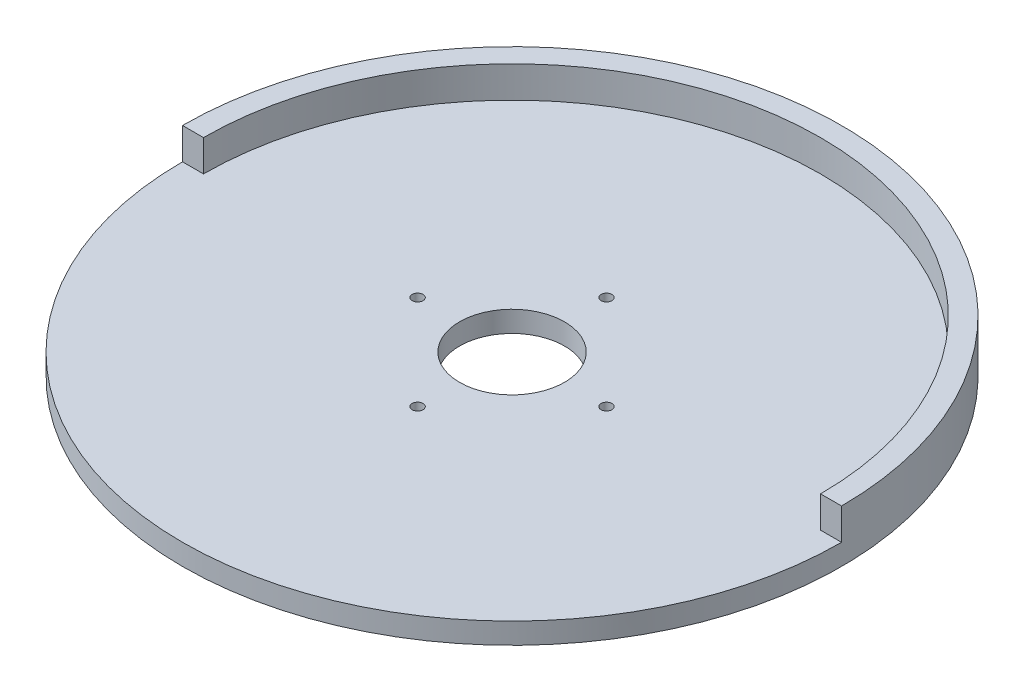
SolidWorks part; units mm, degrees
ref_plane "Front Plane" through (0, 0, 0) normal (0, 0, 1) x (1, 0, 0)
ref_plane "Top Plane" through (0, 0, 0) normal (0, 1, 0) x (1, 0, 0)
ref_plane "Right Plane" through (0, 0, 0) normal (1, 0, 0) x (0, 0, -1)
sketch "Sketch2" plane through (0, 0, 0) normal (0, 1, 0) x (1, 0, 0)
  circle A0 centre (0, 0) radius 65
  circle A1 centre (0, 0) radius 147
  circle A2 centre (0, 0) radius 157
  dimension "D1" = 82
  dimension "D2" = 130
  dimension "D3" = 10
extrude "Boss-Extrude1" add sketch "Sketch2" against normal blind 10 contours A2
sketch "Sketch3" plane through (0, 0, 0) normal (0, 1, 0) x (1, 0, 0)
  line L0 (-157, 0) -> (0, 0)
  line L1 (0, 0) -> (157, 0)
  circle A0 centre (0, 0) radius 147 construction
  circle A1 centre (0, 0) radius 157 construction
  circle A2 centre (0, 0) radius 147
  circle A3 centre (0, 0) radius 157
  circle M3 centre (0, 0) radius 157
extrude "Boss-Extrude2" add sketch "Sketch3" along normal blind 15 contours A2 L1 L0 M3
sketch "Sketch4" plane through (0, 0, 0) normal (0, 1, 0) x (1, 0, 0)
  line L0 (0, 0) -> (0, 8) construction
  circle A0 centre (0, 0) radius 25
  point P5 (0, 0)
  dimension "D1" = 8
  dimension "D2" = 50
extrude "Cut-Extrude1" cut sketch "Sketch4" against normal through all
sketch "Sketch5" plane through (0, -10, 0) normal (0, -1, 0) x (1, 0, 0)
  line L0 (0, 0) -> (0, 45) construction
  circle A0 centre (0, 45) radius 2.6
  dimension "D1" = 5.2
  dimension "D2" = 45
extrude "Cut-Extrude2" cut sketch "Sketch5" against normal through all
pattern_circular "CirPattern1" count 4 over 360 about axis through (0, 0, 0) along (0, 1, 0) of "Cut-Extrude2"
